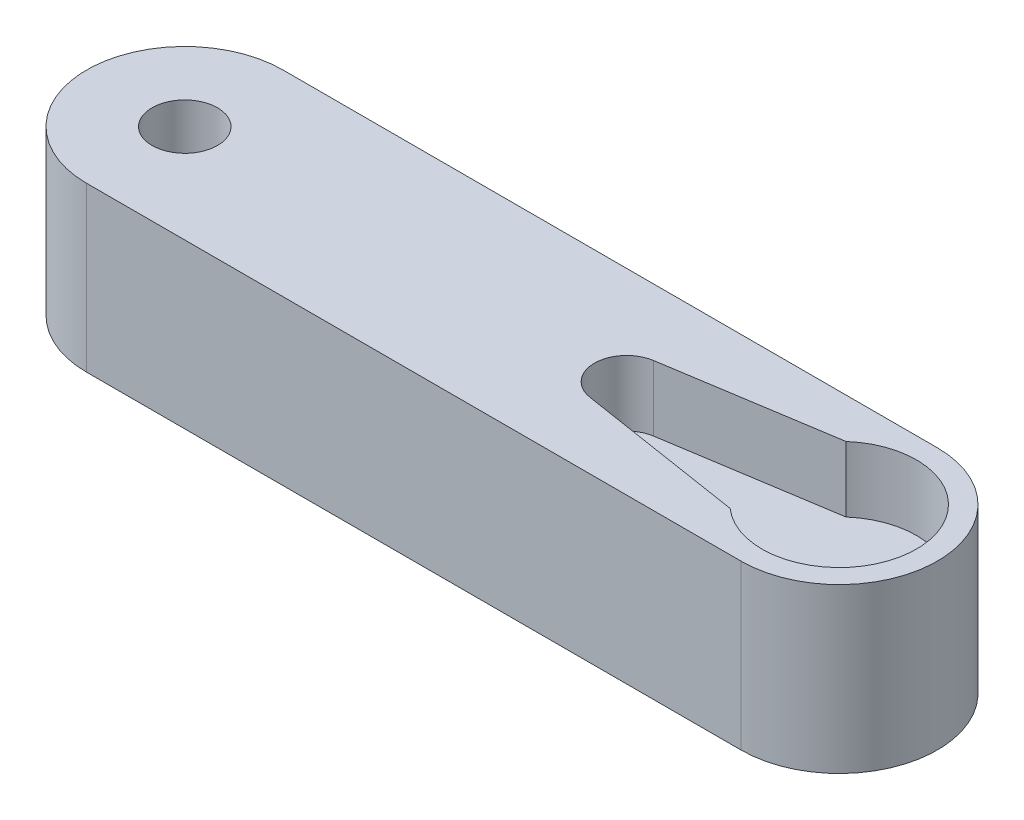
SolidWorks part; units mm, degrees
ref_plane "Front Plane" through (0, 0, 0) normal (0, 0, 1) x (1, 0, 0)
ref_plane "Top Plane" through (0, 0, 0) normal (0, 1, 0) x (1, 0, 0)
ref_plane "Right Plane" through (0, 0, 0) normal (1, 0, 0) x (0, 0, -1)
sketch "Sketch3" plane through (0, 0, 0) normal (0, 1, 0) x (1, 0, 0)
  line L0 (-25.4, 0) -> (25.4, 0) construction
  line L1 (-6.985, 0) -> (6.985, 0) construction
  line L2 (-25.4, 7.62) -> (25.4, 7.62)
  line L3 (-25.4, -7.62) -> (25.4, -7.62)
  arc A0 (-25.4, 7.62) -> (-25.4, -7.62) centre (-25.4, 0) ccw
  arc A1 (25.4, -7.62) -> (25.4, 7.62) centre (25.4, 0) ccw
  point P5 (0, 0)
  dimension "D2" = 7.62
  dimension "D1" = 50.8
  dimension "D3" = 25.4
extrude "Boss-Extrude1" add sketch "Sketch3" along normal blind 12.7
sketch "Sketch4" plane through (0, 12.7, 0) normal (0, 1, 0) x (1, 0, 0)
  circle A0 centre (-25.4, 0) radius 2.54
  dimension "D1" = 5.08
extrude "Cut-Extrude3" cut sketch "Sketch4" against normal through all
sketch "Sketch5" plane through (0, 12.7, 0) normal (0, 1, 0) x (1, 0, 0)
  line L0 (8.5119, -2.4697) -> (21.4314, -4.5)
  line L1 (21.4314, 4.5) -> (8.5119, 2.4697)
  line L2 (-25.4, 0) -> (25.4, 0) construction
  line L3 (-25.4, -7.62) -> (25.4, -7.62) construction
  arc A0 (8.5119, 2.4697) -> (8.5119, -2.4697) centre (8.9, 0) ccw
  arc A1 (21.4314, -4.5) -> (21.4314, 4.5) centre (25.4, 0) ccw
  point P11 (0, 0)
  point P13 (0, 0)
  dimension "D1" = 50.8
  dimension "D2" = 6
  dimension "D6" = 2.5
  dimension "D3" = 8.931
  dimension "D4" = 7.62
  dimension "D5" = 7.62
  dimension "D7" = 8.931
  dimension "D8" = 13.0781
  dimension "D9" = 13.0781
  dimension "D10" = 9
extrude "Cut-Extrude4" cut sketch "Sketch5" against normal blind 5.08
equation "\"TibiaLength\"= 4in"
equation "\"TibiaRadius\"= 0.3in"
equation "\"TibiaDistFromCentre\"= \"TibiaLength\" / 2"
equation "\"TibiaThickness\"= 0.5in"
equation "\"HoleRadius\"= 0.2in"
equation "\"D1@Sketch3\" = \"TibiaLength\" * 0.5"
equation "\"D2@Sketch3\"= \"TibiaRadius\""
equation "\"D3@Sketch3\"=\"TibiaDistFromCentre\"/2"
equation "\"D1@Boss-Extrude1\"= \"TibiaThickness\""
equation "\"D1@Sketch4\"= \"HoleRadius\""
equation "\"D1@Sketch5\"=\"TibiaLength\"/2"
